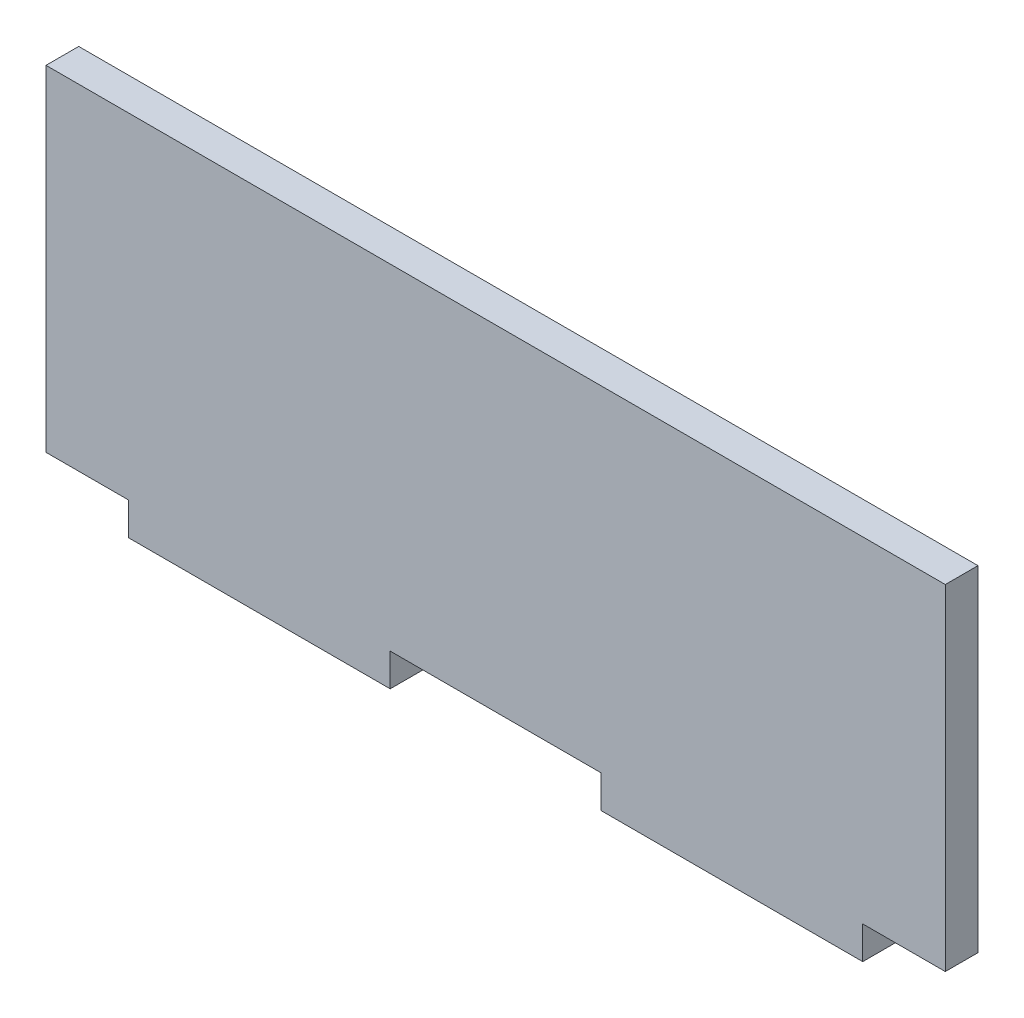
SolidWorks part; units mm, degrees
ref_plane "Front Plane" through (0, 0, 0) normal (0, 0, 1) x (1, 0, 0)
ref_plane "Top Plane" through (0, 0, 0) normal (0, 1, 0) x (1, 0, 0)
ref_plane "Right Plane" through (0, 0, 0) normal (1, 0, 0) x (0, 0, -1)
sketch "Sketch1" plane through (0, 0, 0) normal (0, 0, 1) x (1, 0, 0)
  line L0 (0, 10.25) -> (0, -14.4509) construction
  line L1 (-27.5, -10.25) -> (27.5, -10.25)
  line L2 (-27.5, -10.25) -> (-27.5, 10.25)
  line L3 (-27.5, 10.25) -> (27.5, 10.25)
  line L4 (27.5, -10.25) -> (27.5, 10.25)
  line L5 (-27.5, -10.25) -> (27.5, 10.25) construction
  line L6 (-27.5, 10.25) -> (27.5, -10.25) construction
  line L7 (22.45, -10.25) -> (22.45, -12.25)
  line L8 (-22.45, -10.25) -> (-6.45, -10.25)
  line L9 (-22.45, -10.25) -> (-22.45, -12.25)
  line L10 (-22.45, -12.25) -> (-6.45, -12.25)
  line L11 (-6.45, -10.25) -> (-6.45, -12.25)
  line L12 (22.45, -12.25) -> (6.45, -12.25)
  line L13 (6.45, -10.25) -> (6.45, -12.25)
  point P0 (0, 0)
  dimension "D1" = 55
  dimension "D2" = 20.5
  dimension "D3" = 2
  dimension "D4" = 16
  dimension "D5" = 5.05
extrude "Boss-Extrude1" add sketch "Sketch1" along normal blind 2 contours L1 L4 L3 L2 | L11 L1 L9 L10 | L1 L13 L12 L7
